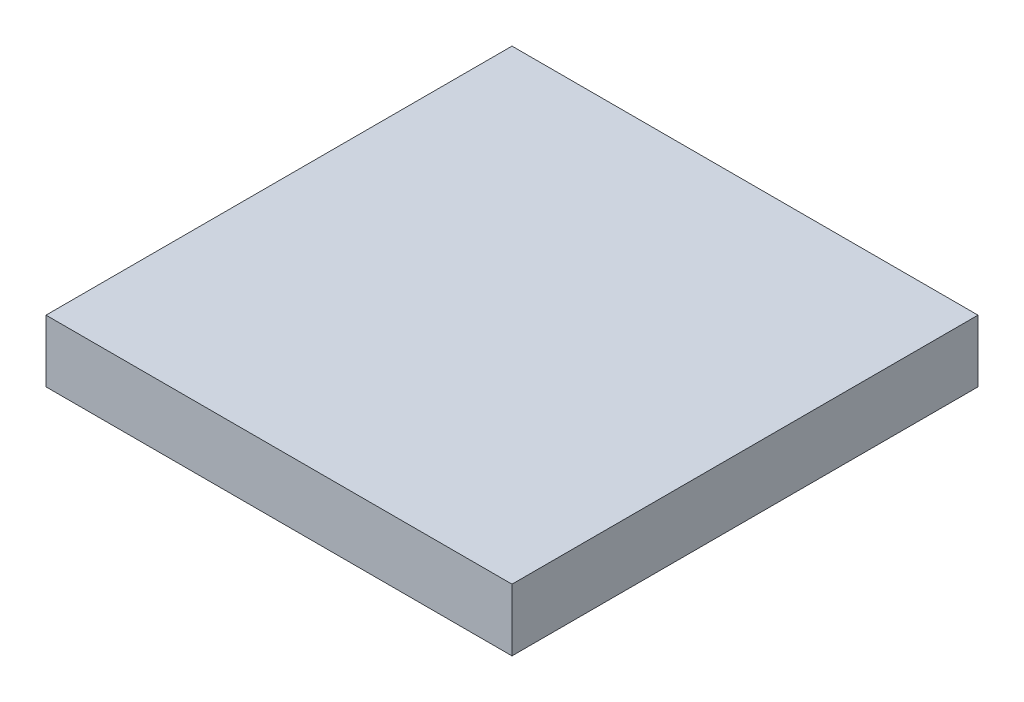
SolidWorks part; units mm, degrees
ref_plane "Front Plane" through (0, 0, 0) normal (0, 0, 1) x (1, 0, 0)
ref_plane "Top Plane" through (0, 0, 0) normal (0, 1, 0) x (1, 0, 0)
ref_plane "Right Plane" through (0, 0, 0) normal (1, 0, 0) x (0, 0, -1)
sketch "Sketch1" plane through (0, 0, 0) normal (0, 1, 0) x (1, 0, 0)
  line L1 (-25.5294, 13.451) -> (-10.5294, 13.451)
  line L2 (-25.5294, 13.451) -> (-25.5294, -1.549)
  line L3 (-25.5294, -1.549) -> (-10.5294, -1.549)
  line L4 (-10.5294, 13.451) -> (-10.5294, -1.549)
  dimension "D1" = 15
  dimension "D2" = 15
extrude "Boss-Extrude1" add sketch "Sketch1" along normal blind 2
